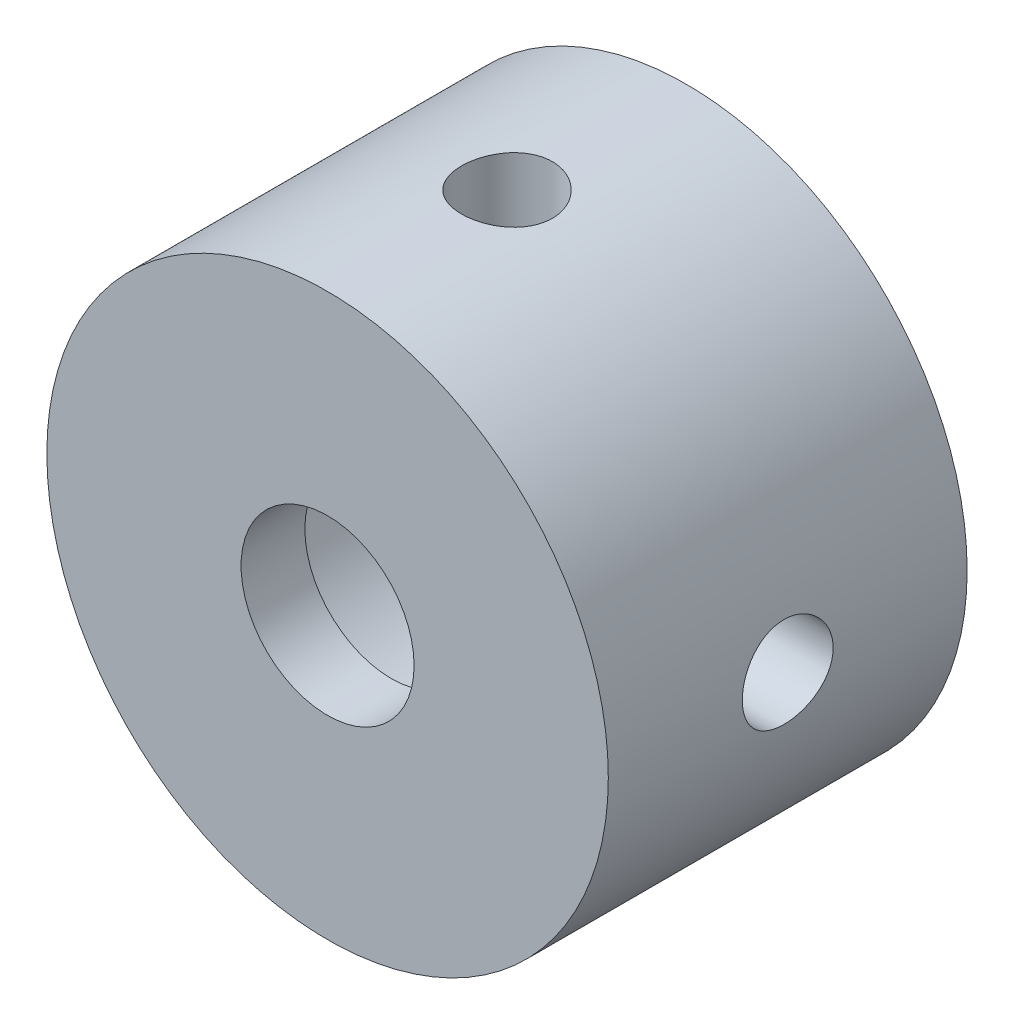
SolidWorks part; units mm, degrees
material "6061-T6 (SS)"
ref_plane "Front Plane" through (0, 0, 0) normal (0, 0, 1) x (1, 0, 0)
ref_plane "Top Plane" through (0, 0, 0) normal (0, 1, 0) x (1, 0, 0)
ref_plane "Right Plane" through (0, 0, 0) normal (1, 0, 0) x (0, 0, -1)
sketch "Sketch1" plane through (0, 0, 0) normal (1, 0, 0) x (0, 0, -1)
  line L0 (0, 0) -> (0, 2.7375) construction
  line L1 (0, 6.35) -> (3.175, 6.35)
  line L2 (3.175, 6.35) -> (3.175, 5.5315)
  line L3 (5.7937, 8.5) -> (5.7937, 13) construction
  line L4 (5.7937, 13) -> (0.7938, 13) construction
  line L5 (0.7938, 13) -> (0.7938, 8.5) construction
  line L6 (5.7937, 13) -> (5.7937, 14) construction
  line L7 (5.7937, 14) -> (6.7937, 14) construction
  line L8 (6.7937, 14) -> (6.7937, 7.5) construction
  line L9 (0, 8.5) -> (5.7937, 8.5)
  line L10 (0, 8.5) -> (0, 6.35) construction
  line L11 (5.7937, 8.5) -> (5.7937, 7.5)
  line L12 (5.7937, 7.5) -> (39.6687, 7.5)
  line L13 (6.7937, 14) -> (6.7937, 20.32) construction
  line L14 (6.7937, 20.32) -> (16.3187, 20.32) construction
  line L15 (16.3187, 20.32) -> (16.3187, 7.5) construction
  line L16 (11.5562, 19.5) -> (11.5562, 7.5) construction
  line L17 (11.5562, 19.5) -> (16.5562, 19.5) construction
  line L18 (16.5562, 19.5) -> (16.5562, 7.5) construction
  line L19 (9.175, 20.32) -> (9.175, 0) construction
  line L20 (16.5562, 19.5) -> (16.5562, 14) construction
  line L21 (16.5562, 14) -> (17.5562, 14) construction
  line L22 (17.5562, 14) -> (17.5562, 7.5) construction
  line L23 (0, 0) -> (31.9294, 0)
  line L24 (17.5562, 14) -> (17.5562, 26.67) construction
  line L25 (17.5562, 26.67) -> (27.0812, 26.67) construction
  line L26 (27.0812, 26.67) -> (27.0812, 7.5) construction
  line L27 (22.3187, 7.5) -> (22.3187, 19.5) construction
  line L28 (22.3187, 19.5) -> (27.3187, 19.5) construction
  line L29 (27.3187, 19.5) -> (27.3187, 7.5) construction
  line L30 (19.9375, 26.67) -> (19.9375, 0) construction
  line L31 (27.3187, 19.5) -> (27.3187, 14) construction
  line L32 (27.3187, 14) -> (28.3187, 14) construction
  line L33 (28.3187, 14) -> (28.3187, 7.5) construction
  line L34 (28.3187, 19.5) -> (33.3187, 19.5) construction
  line L35 (33.3187, 19.5) -> (33.3187, 7.5) construction
  line L36 (33.3187, 2.3813) -> (33.3187, 38.6538) construction
  line L37 (26.9687, 0) -> (26.9687, 30.1625) construction
  line L38 (28.5562, 30.1625) -> (28.5562, 0) construction
  line L39 (0, 0) -> (0, 2.7375) construction
  line L40 (6.35, 42.8625) -> (6.35, 0) construction
  line L41 (4.7625, 50.8) -> (4.7625, 0) construction
  line L42 (-17.4625, 46.0375) -> (-17.4625, 53.5375)
  line L43 (3.175, 5.5315) -> (23.1125, 5.5315)
  line L44 (0, 4.7378) -> (13.0644, 4.7378) construction
  line L45 (0, 2.7375) -> (14.0479, 2.7375)
  line L46 (11.9076, 4.7378) -> (9.9073, 2.7375) construction
  line L47 (17.2049, 4.7378) -> (19.2052, 2.7375) construction
  line L48 (21.1281, 4.7378) -> (23.1284, 2.7375)
  line L49 (16.0481, 4.7378) -> (16.0481, 0) construction
  line L50 (7.9844, 4.7378) -> (5.9841, 2.7375) construction
  line L51 (13.0644, 4.7378) -> (15.0646, 2.7375) construction
  line L52 (16.0481, 4.7378) -> (14.0479, 2.7375)
  line L53 (29.1919, 2.7375) -> (31.9294, 0)
  line L54 (16.0481, 4.7378) -> (21.1281, 4.7378)
  line L55 (39.6687, 2.3813) -> (39.6687, 7.5)
  line L56 (0, 6.35) -> (0, 44.45) construction
  line L57 (23.1284, 2.7375) -> (29.1919, 2.7375)
  line L58 (23.1125, 5.5315) -> (24.5284, 3.175)
  line L59 (24.5284, 3.175) -> (29.8649, 3.175)
  line L60 (29.8649, 3.175) -> (30.3419, 2.3813)
  line L61 (30.3419, 2.3813) -> (39.6687, 2.3813)
  line L62 (30.3419, 2.3813) -> (29.5481, 2.3813)
  line L63 (0, 2.7375) -> (-3.175, 2.7375)
  line L64 (-3.175, 2.7375) -> (-3.175, 2)
  line L65 (-3.175, 2) -> (-9.9531, 2)
  line L66 (-9.9531, 2) -> (-9.9531, 0)
  line L67 (-9.9531, 0) -> (0, 0)
  line L68 (-3.175, 2.7375) -> (-3.175, 4.5)
  line L69 (-3.175, 4.5) -> (-7.175, 4.5)
  line L70 (-7.175, 4.5) -> (-7.175, 2)
  line L71 (-3.175, 3.5) -> (-1.5875, 3.5)
  line L72 (-1.5875, 3.5) -> (-1.5875, 8.5)
  line L73 (-1.5875, 8.5) -> (-16.1031, 8.5)
  line L74 (-14.5156, 3.429) -> (-14.5156, 3.81)
  line L75 (-14.5156, 3.81) -> (-7.175, 3.81)
  line L76 (-7.302, 0) -> (-7.302, 3.175)
  line L77 (-7.302, 3.175) -> (-8.8895, 3.175)
  line L78 (-8.8895, 3.175) -> (-8.8895, 0)
  line L79 (-10.35, 0) -> (-10.35, 3.429)
  line L80 (-10.35, 3.429) -> (-14.5156, 3.429)
  line L81 (-14.5156, 3.429) -> (-14.5156, 0)
  line L82 (-14.5156, 0) -> (-10.35, 0)
  line L83 (-7.175, 4.5) -> (-7.175, 6.985)
  line L84 (-7.175, 6.985) -> (-16.1031, 6.985)
  line L85 (-16.1031, 6.985) -> (-16.1031, 8.5)
  line L86 (-16.1031, 0) -> (-16.1031, 6.985)
  line L87 (-14.5156, 0) -> (-16.1031, 0)
  circle A0 centre (-17.4625, 46.0375) radius 7.5
  circle A1 centre (-17.4625, 46.0375) radius 5.5315
  circle A2 centre (-17.4625, 53.1565) radius 2.3812
  circle A3 centre (-17.4625, 51.1562) radius 2.3812
  circle A4 centre (-17.4625, 46.0375) radius 12.7
  arc A5 (-14.9548, 53.1058) -> (-19.9702, 53.1058) centre (-17.4625, 53.1565) ccw
  circle A6 centre (-17.4625, 46.0375) radius 2.7375
  circle A7 centre (-17.4625, 46.0375) radius 4.7378
  circle A8 centre (-17.4625, 46.0375) radius 7.754
  circle A9 centre (9.175, 7.119) radius 2.3813 construction
  circle A10 centre (9.175, 5.3727) radius 2.3813 construction
  circle A11 centre (9.175, 5.1187) radius 2.3813 construction
  circle A12 centre (19.9375, 7.119) radius 2.3813 construction
  circle A13 centre (19.9375, 5.3727) radius 2.3813 construction
  circle A14 centre (19.9375, 5.1187) radius 2.3813 construction
  dimension "D24" = 15
  dimension "D25" = 4.7625
  dimension "D27" = 25.4
  dimension "D28" = 5.0165
  dimension "D29" = 0.7937
  dimension "D30" = 0.254
  dimension "D31" = 11.063
  dimension "D32" = 5.475
  dimension "D34" = 9.4755
  dimension "D37" = 4.7625
  dimension "D39" = 2.1273
  dimension "D1" = 8.5
  dimension "D2" = 3.175
  dimension "D3" = 6.35
  dimension "D4" = 5.7937
  dimension "D5" = 7.5
  dimension "D6" = 5
  dimension "D7" = 13
  dimension "D8" = 1
  dimension "D9" = 14
  dimension "D10" = 9.525
  dimension "D11" = 20.32
  dimension "D12" = 4.7625
  dimension "D13" = 5
  dimension "D14" = 2.3813
  dimension "D15" = 12
  dimension "D16" = 26.67
  dimension "D17" = 4.7625
  dimension "D18" = 2.3813
  dimension "D19" = 6.35
  dimension "D20" = 1.5875
  dimension "D21" = 6.35
  dimension "D22" = 1.5875
  dimension "D23" = 6.35
  dimension "D26" = 0.381
  dimension "D33" = 5.5315
  dimension "D35" = 4.7378
  dimension "D36" = 2.7375
  dimension "D38" = 0.381
  dimension "D40" = 45
  dimension "D41" = 5.2973
  dimension "D42" = 10.7625
  dimension "D43" = 1.1906
  dimension "D44" = 5.08
  dimension "D45" = 1.1906
  dimension "D46" = 8.0637
  dimension "D47" = 5.08
  dimension "D48" = 6.0635
  dimension "D49" = 45
  dimension "D50" = 6.0635
  dimension "D51" = 0.7937
  dimension "D52" = 59
  dimension "D53" = 3.175
  dimension "D54" = 0.7937
  dimension "D55" = 2.3813
  dimension "D56" = 2
  dimension "D57" = 4.5
  dimension "D58" = 4
  dimension "D59" = 1.5875
  dimension "D60" = 4.69
  dimension "D61" = 1.5875
  dimension "D62" = 4.1656
  dimension "D63" = 3.429
  dimension "D64" = 2.7781
  dimension "D65" = 1.5875
  dimension "D66" = 3.175
  dimension "D67" = 0.127
  dimension "D68" = 0.3969
  dimension "D69" = 1.5875
  dimension "D70" = 3.81
  dimension "D71" = 3.175
  dimension "D73" = 14.5156
  dimension "D74" = 1
revolve "Revolve1" add sketch "Sketch1" angle 360 about L67
sketch "Sketch2" plane through (0, 0, 16.1031) normal (0, 0, 1) x (1, 0, 0)
  point P0 (0, 0)
hole_wizard "#8 Clearance Hole1" positions "Sketch6" profile "Sketch7" hole size "#8" standard "ANSI Inch" end condition through all
sketch "Sketch6" plane through (0, 0, 16.1031) normal (0, 0, 1) x (1, 0, 0)
  point P0 (0, 0)
sketch "Sketch7" plane through (0, 0, 16.1031) normal (1, 0, 0) x (0, -1, 0)
  line L0 (0, 0) -> (0, 8.9281)
  line L1 (0, 8.9281) -> (2.1526, 8.9281)
  line L2 (2.1526, 8.9281) -> (2.1526, 0)
  line L5 (2.1526, 0) -> (0, 0)
  line L11 (0, -6.35) -> (0, 107.95) construction
  dimension "Thru Hole Dia." = 4.3053
  dimension "Thru Hole Depth" = 8.9281
ref_plane "Plane1" through (0, 6.985, 0) normal (0, 1, 0) x (1, 0, 0)
sketch "Sketch8" plane through (0, 6.985, 0) normal (0, 1, 0) x (1, 0, 0)
  line L0 (6.985, -7.175) -> (-6.985, -7.175) construction
  line L1 (-6.985, -16.1031) -> (6.985, -16.1031) construction
  line L2 (6.985, -7.175) -> (-6.985, -7.175)
  line L3 (-6.985, -16.1031) -> (6.985, -16.1031)
  line L4 (0, -7.175) -> (0, -16.1031)
  point P6 (0, -11.6391)
hole_wizard "#4-40 Tapped Hole1" positions "Sketch10" profile "Sketch9" tap size "#4-40" standard "ANSI Inch"
sketch "Sketch10" plane through (0, 6.985, 0) normal (0, 1, 0) x (1, 0, 0)
  point P0 (0, -11.6391)
sketch "Sketch9" plane through (0, 6.985, 11.6391) normal (1, 0, 0) x (0, 0, 1)
  line L0 (0, 0) -> (0, 10.796)
  line L1 (0, 10.796) -> (1.1303, 10.796)
  line L2 (1.1303, 10.796) -> (1.1303, 0)
  line L5 (1.1303, 0) -> (0, 0)
  line L11 (0, -6.35) -> (0, 107.95) construction
  dimension "Thru Tap Drill Dia." = 2.2606
  dimension "Thru Tap Drill Depth" = 10.796
cosmetic thread "Hole Thread1" parameters "D2"=2.8448
pattern_circular "CirPattern1" count 4 over 360 about axis through (0, 0, 9.9531) along (0, 0, 1) of "#4-40 Tapped Hole1"
equation "\"D1@Sketch1\"=(17mm/2)"
equation "\"D5@Sketch1\"=15mm/2"
equation "\"D4@Sketch1\"=5mm+1/32"
equation "\"D6@Sketch1\"=5mm"
equation "\"D7@Sketch1\"=26mm/2"
equation "\"D8@Sketch1\"=1mm"
equation "\"D9@Sketch1\"=28mm/2"
equation "\"D11@Sketch1\"=(34-2)/20/2"
equation "\"D13@Sketch1\"=5mm"
equation "\"D15@Sketch1\"=24mm/2"
equation "\"D16@Sketch1\"=(44-2)/20/2"
equation "\"D33@Sketch1\"=\"D31@Sketch1\"/2"
equation "\"D35@Sketch1\"= \"D34@Sketch1\" / 2"
equation "\"D36@Sketch1\"= \"D32@Sketch1\" / 2"
equation "\"D39@Sketch1\" = \"D37@Sketch1\"/2-.01"
equation "\"D45@Sketch1\" = 3 / 64"
equation "\"D43@Sketch1\" = \"D45@Sketch1\""
equation "\"D47@Sketch1\"=\"D44@Sketch1\""
equation "\"D56@Sketch1\"=2mm"
equation "\"D57@Sketch1\"=9mm/2"
equation "\"D58@Sketch1\"=4mm"
equation "\"D63@Sketch1\"=.27/2"
equation "\"D64@Sketch1\"=1/16+3/64"
equation "\"D74@Sketch1\"=1mm"
